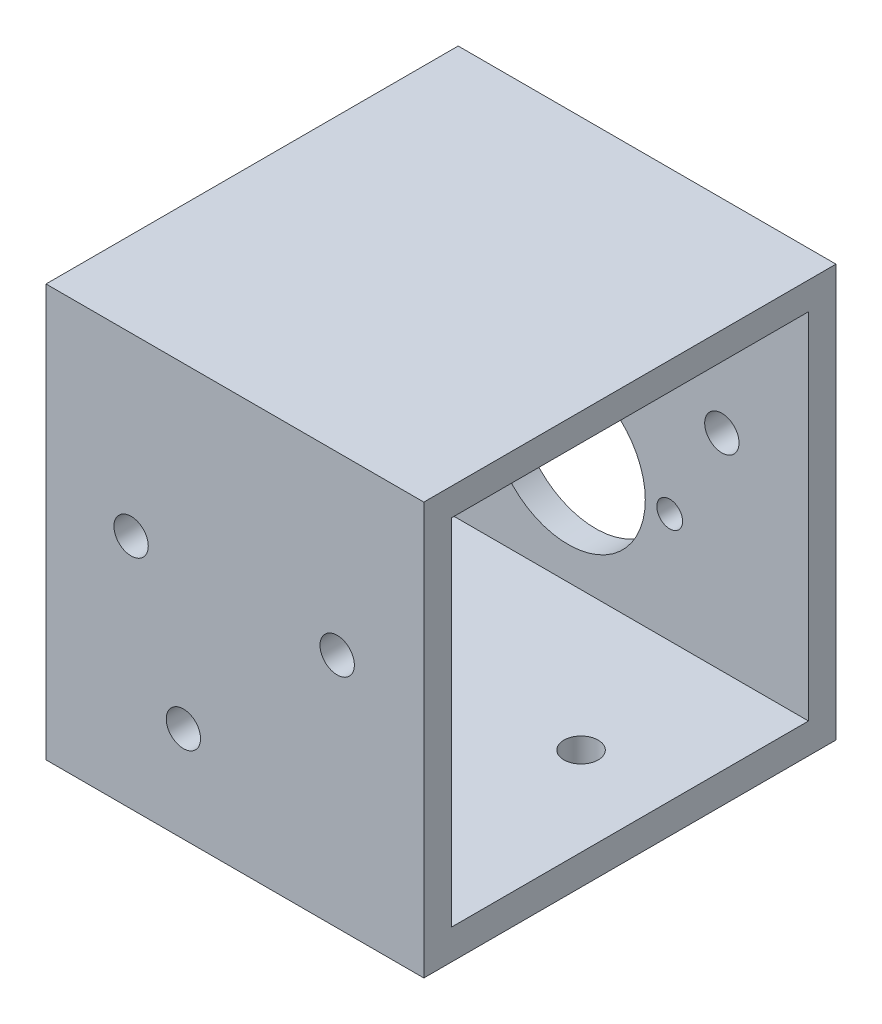
SolidWorks part; units mm, degrees
ref_plane "Front Plane" through (0, 0, 0) normal (0, 0, 1) x (1, 0, 0)
ref_plane "Top Plane" through (0, 0, 0) normal (0, 1, 0) x (1, 0, 0)
ref_plane "Right Plane" through (0, 0, 0) normal (1, 0, 0) x (0, 0, -1)
sketch "Sketch1" plane through (0, 0, 0) normal (0, 0, 1) x (1, 0, 0)
  line L0 (-25.4, 43.942) -> (-25.4, 50.292)
  line L1 (-25.4, -25.908) -> (44.45, -25.908)
  line L2 (-25.4, -25.908) -> (-25.4, 43.942)
  line L3 (-13.335, 50.292) -> (-38.735, 50.292) construction
  line L4 (44.45, -25.908) -> (44.45, 24.892)
  line L7 (-25.4, 50.292) -> (44.45, 50.292)
  line L8 (38.735, 50.292) -> (13.335, 50.292) construction
  line L9 (44.45, 50.292) -> (44.45, 24.892)
  circle A0 centre (0, 0) radius 14.2748 construction
  circle A1 centre (0, 0) radius 14.2748
  circle A2 centre (18.7833, 0) radius 2.3876 construction
  circle A3 centre (-18.7833, 0) radius 2.3876 construction
  circle A4 centre (18.7833, 0) radius 2.3876
  circle A5 centre (-18.7833, 0) radius 2.3876
  circle A6 centre (28.4309, 17.78) radius 3.175
  dimension "D1" = 76.2
  dimension "D2" = 69.85
extrude "Boss-Extrude1" add sketch "Sketch1" along normal blind 3.81 and the other way blind 1.27
sketch "Sketch2" plane through (0, 0, 3.81) normal (0, 0, 1) x (1, 0, 0)
  line L0 (44.45, -25.908) -> (44.45, 50.292) construction
  line L1 (-25.4, 50.292) -> (44.45, 50.292)
  line L2 (-25.4, 50.292) -> (-25.4, 45.212)
  line L3 (-25.4, 45.212) -> (44.45, 45.212)
  line L4 (44.45, 50.292) -> (44.45, 45.212)
extrude "Boss-Extrude2" add sketch "Sketch2" along normal blind 66.04
sketch "Sketch3" plane through (0, 0, 3.81) normal (0, 0, 1) x (1, 0, 0)
  line L0 (44.45, -25.908) -> (44.45, 45.212) construction
  line L1 (-25.4, -25.908) -> (44.45, -25.908)
  line L2 (-25.4, -25.908) -> (-25.4, -20.32)
  line L3 (-25.4, -20.32) -> (44.45, -20.32)
  line L4 (44.45, -25.908) -> (44.45, -20.32)
extrude "Boss-Extrude3" add sketch "Sketch3" along normal blind 66.04
sketch "Sketch4" plane through (0, 0, 69.85) normal (0, 0, 1) x (1, 0, 0)
  line L0 (8.5687, -5.08) -> (7.8718, -5.08) construction
  line L1 (-25.4, 50.292) -> (44.45, 50.292)
  line L2 (-25.4, 50.292) -> (-25.4, -25.908)
  line L3 (-25.4, -25.908) -> (44.45, -25.908)
  line L4 (44.45, 50.292) -> (44.45, -25.908)
  circle A0 centre (28.4309, 17.78) radius 3.175
  circle A1 centre (0, -8.2296) radius 3.175 construction
  circle A2 centre (0, -8.2296) radius 3.175
  dimension "D1" = 22.86
extrude "Boss-Extrude4" add sketch "Sketch4" along normal blind 5.08
sketch "Sketch6" plane through (0, -25.908, 0) normal (0, -1, 0) x (1, 0, 0)
  line L0 (44.45, -1.27) -> (44.45, 74.93) construction
  line L1 (44.45, -1.27) -> (-25.4, -1.27) construction
  circle A0 centre (28.0688, 29.4788) radius 3.175
  dimension "D1" = 16.3812
  dimension "D2" = 30.7488
extrude "Cut-Extrude1" cut sketch "Sketch6" against normal up to next
sketch "Sketch7" plane through (-25.4, 0, 0) normal (-1, 0, 0) x (0, 0, 1)
  line L0 (69.85, 45.212) -> (3.81, 45.212) construction
  line L1 (69.85, 45.212) -> (69.85, -20.32) construction
  line L2 (3.81, 45.212) -> (3.81, -20.32) construction
  line L3 (69.85, -20.32) -> (3.81, -20.32) construction
  line L4 (-1.27, -25.908) -> (74.93, -25.908)
  line L5 (74.93, -25.908) -> (74.93, 50.292)
  line L6 (74.93, 50.292) -> (-1.27, 50.292)
  line L7 (-1.27, 50.292) -> (-1.27, -25.908)
  line L8 (-1.27, -25.908) -> (74.93, -25.908)
  line L9 (74.93, -25.908) -> (74.93, 50.292)
  line L10 (74.93, 50.292) -> (-1.27, 50.292)
  line L11 (-1.27, 50.292) -> (-1.27, -25.908)
  line L12 (69.85, 45.212) -> (3.81, 45.212)
  line L13 (69.85, 45.212) -> (69.85, -20.32)
  line L14 (3.81, 45.212) -> (3.81, -20.32)
  line L15 (69.85, -20.32) -> (3.81, -20.32)
  dimension "D1" = 0
sketch "Sketch8" plane through (0, 0, 74.93) normal (0, 0, 1) x (1, 0, 0)
  line L0 (0, -1000) -> (0, 49000) construction
  circle A0 centre (-9.6691, 17.78) radius 3.175
  circle A2 centre (28.4309, 17.78) radius 3.175 construction
  dimension "D1" = 38.1
extrude "Cut-Extrude2" cut sketch "Sketch8" against normal through all
